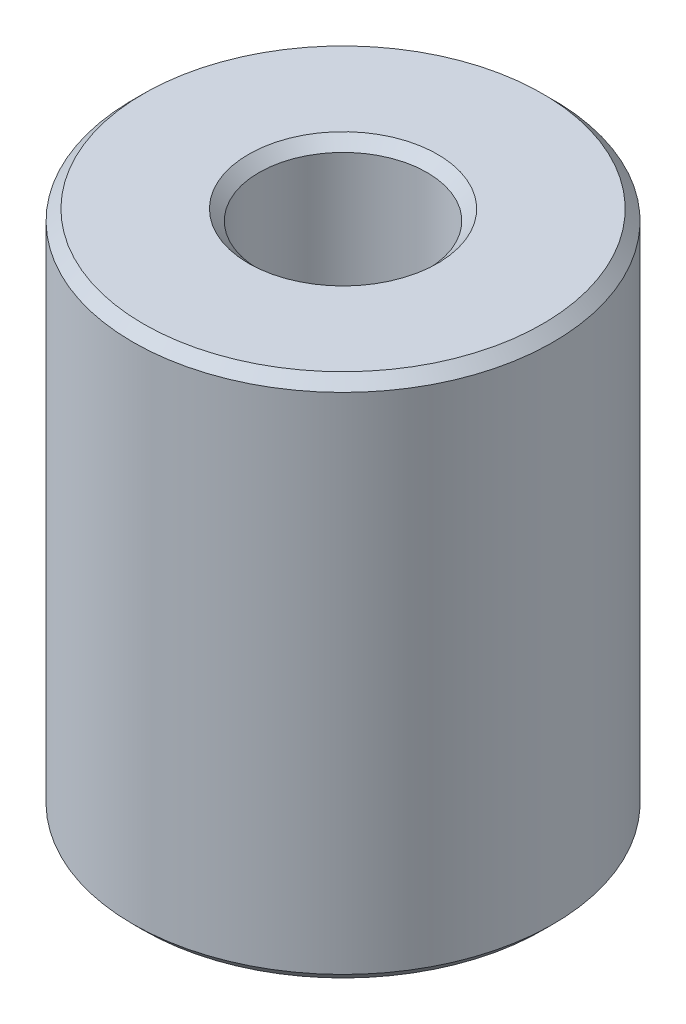
SolidWorks part; units mm, degrees
ref_plane "Front Plane" through (0, 0, 0) normal (0, 0, 1) x (1, 0, 0)
ref_plane "Top Plane" through (0, 0, 0) normal (0, 1, 0) x (1, 0, 0)
ref_plane "Right Plane" through (0, 0, 0) normal (1, 0, 0) x (0, 0, -1)
sketch "Sketch1" plane through (0, 0, 0) normal (0, 1, 0) x (1, 0, 0)
  circle A0 centre (0, 0) radius 10
  dimension "D1" = 20
extrude "Boss-Extrude1" add sketch "Sketch1" along normal blind 25
sketch "Sketch2" plane through (0, 25, 0) normal (0, 1, 0) x (1, 0, 0)
  circle A0 centre (0, 0) radius 4
  dimension "D1" = 8
extrude "Cut-Extrude1" cut sketch "Sketch2" against normal blind 10
sketch "Sketch3" plane through (0, 0, 0) normal (0, -1, 0) x (1, 0, 0)
  circle A0 centre (0, 0) radius 2.5
  dimension "D1" = 5
extrude "Cut-Extrude2" cut sketch "Sketch3" against normal blind 10
chamfer "Chamfer1" distance 0.5 angle 45 4 edges at (0, 0, -2.5) (0, 0, 10) (0, 25, 4) (0, 25, 10)
